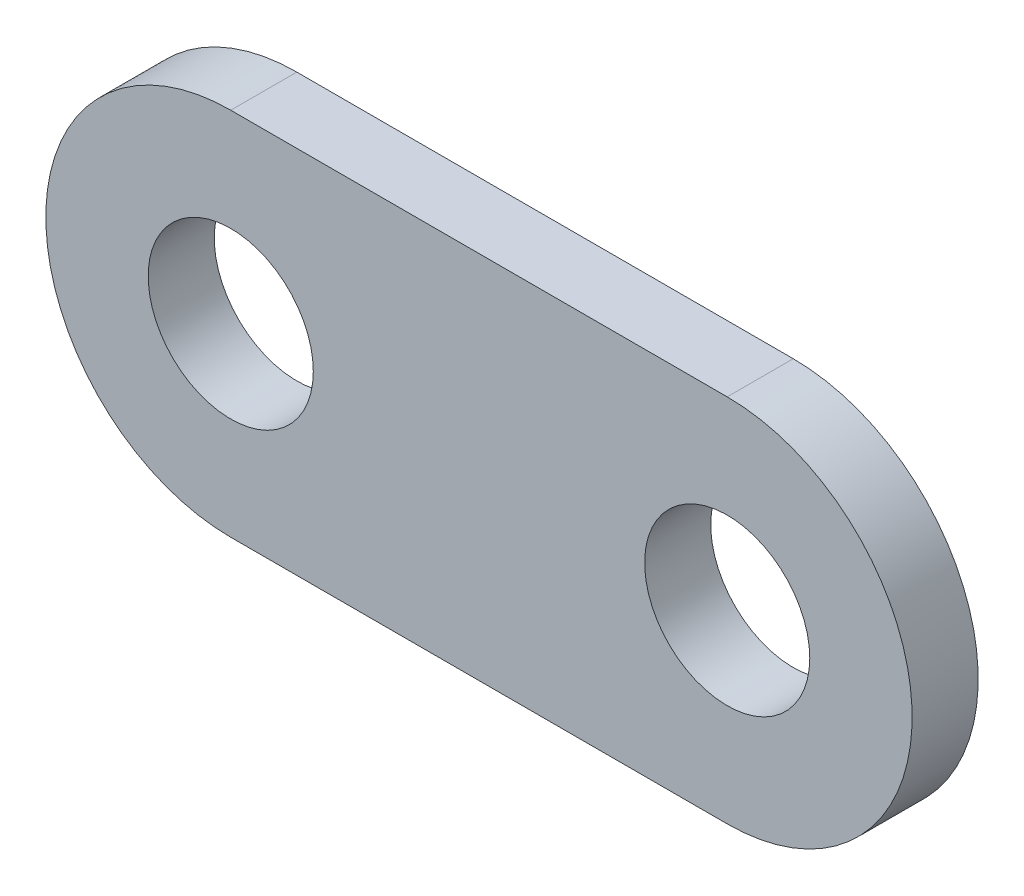
SolidWorks part; units mm, degrees
material "Hexcel AS4C (3000 丝)"
ref_plane "前视基准面" through (0, 0, 0) normal (0, 0, 1) x (1, 0, 0)
ref_plane "上视基准面" through (0, 0, 0) normal (0, 1, 0) x (1, 0, 0)
ref_plane "右视基准面" through (0, 0, 0) normal (1, 0, 0) x (0, 0, -1)
sketch "草图1" plane through (0, 0, 0) normal (0, 0, 1) x (1, 0, 0)
  line L0 (3.7585, -94.7152) -> (-3.7585, -94.7152)
  line L1 (3.7585, -100.3152) -> (-3.7585, -100.3152)
  circle A0 centre (3.7585, -97.5152) radius 1.25 construction
  circle A1 centre (-3.7585, -97.5152) radius 1.25 construction
  circle A6 centre (3.7585, -97.5152) radius 1.25
  circle A7 centre (-3.7585, -97.5152) radius 1.25
  arc A8 (3.7585, -94.7152) -> (3.7585, -100.3152) centre (3.7585, -97.5152) cw
  arc A9 (-3.7585, -94.7152) -> (-3.7585, -100.3152) centre (-3.7585, -97.5152) ccw
  point P2 (3.7585, -94.9881)
  point P18 (0, 0)
  point P19 (0, 0)
extrude "凸台-拉伸1" add sketch "草图1" along normal blind 1
